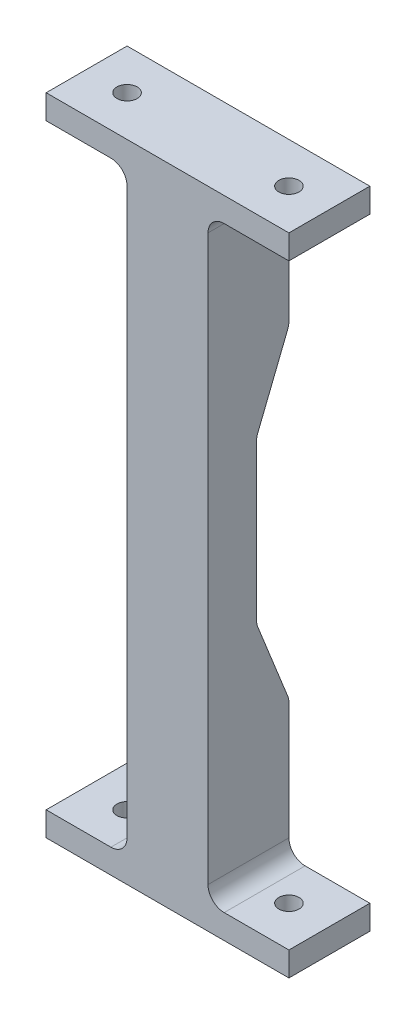
SolidWorks part; units mm, degrees
material "PLA"
ref_plane "Front Plane" through (0, 0, 0) normal (0, 0, 1) x (1, 0, 0)
ref_plane "Top Plane" through (0, 0, 0) normal (0, 1, 0) x (1, 0, 0)
ref_plane "Right Plane" through (0, 0, 0) normal (1, 0, 0) x (0, 0, -1)
sketch "Sketch1" plane through (0, 0, 0) normal (0, 0, 1) x (1, 0, 0)
  line L0 (19.05, 0) -> (-19.05, 0)
  line L1 (-19.05, 0) -> (-19.05, 3.81)
  line L2 (-19.05, 3.81) -> (-6.35, 3.81)
  line L3 (-6.35, 3.81) -> (-6.35, 97.4598)
  line L4 (-6.35, 97.4598) -> (-19.05, 97.4598)
  line L5 (-19.05, 97.4598) -> (-19.05, 101.2698)
  line L6 (-19.05, 101.2698) -> (19.05, 101.2698)
  line L7 (0, 101.2698) -> (0, 0) construction
  line L8 (19.05, 97.4598) -> (19.05, 101.2698)
  line L9 (6.35, 97.4598) -> (19.05, 97.4598)
  line L10 (6.35, 3.81) -> (6.35, 97.4598)
  line L11 (19.05, 3.81) -> (6.35, 3.81)
  line L12 (19.05, 0) -> (19.05, 3.81)
  dimension "D1" = 12.7
  dimension "D2" = 3.81
  dimension "D3" = 3.81
  dimension "D4" = 101.2698
  dimension "D5" = 12.7
  dimension "D6" = 12.7
extrude "Boss-Extrude1" add sketch "Sketch1" along normal mid plane 12.7
sketch "Sketch2" plane through (0, 3.81, 0) normal (0, 1, 0) x (1, 0, 0)
  line L0 (6.35, 6.35) -> (6.35, -6.35) construction
  line L1 (6.35, 0) -> (19.05, 0) construction
  line L2 (19.05, -6.35) -> (19.05, 6.35) construction
  line L3 (0, 0) -> (0, -6.35) construction
  line L4 (19.05, -6.35) -> (-19.05, -6.35) construction
  circle A0 centre (12.7, 0) radius 1.5875
  circle A1 centre (-12.7, 0) radius 1.5875
  dimension "D1" = 3.175
  dimension "D2" = 25.4
extrude "Mount_Holes" cut sketch "Sketch2" against normal blind 12.7
ref_plane "MidPlane" through (0, 50.6349, 0) normal (0, 1, 0) x (1, 0, 0)
mirror "Mirror1" about plane through (0, 50.6349, 0) normal (0, 1, 0) of "Mount_Holes"
fillet "Fillet1" radius 2.54 4 edges at (6.35, 3.81, 0) (-6.35, 3.81, 0) (-6.35, 97.4598, 0) (6.35, 97.4598, 0)
sketch "Sketch3" plane through (-6.35, 0, 0) normal (-1, 0, 0) x (0, 0, 1)
  line L0 (-6.35, 25.2349) -> (-6.35, 76.0349)
  line L1 (-6.35, 94.9198) -> (-6.35, 6.35) construction
  line L2 (-6.35, 76.0349) -> (-1.27, 63.3349)
  line L3 (-1.27, 63.3349) -> (-1.27, 37.9349)
  line L4 (6.985, 50.6349) -> (-6.985, 50.6349) construction
  line L6 (-6.35, 25.2349) -> (-1.27, 37.9349)
  line L7 (6.35, 94.9198) -> (6.35, 6.35) construction
  point P9 (-1.27, 50.6349)
  point P10 (-6.35, 50.6349)
  dimension "D1" = 50.8
  dimension "D2" = 25.4
  dimension "D3" = 7.62
extrude "Cut-Extrude1" cut sketch "Sketch3" against normal through all
fillet "Fillet2" radius 2.54 4 edges at (0, 76.0349, -6.35) (0, 63.3349, -1.27) (0, 37.9349, -1.27) (0, 25.2349, -6.35)
equation "\"D3@Sketch1\"=\"D2@Sketch1\""
equation "\"D6@Sketch1\"=\"D5@Sketch1\""
